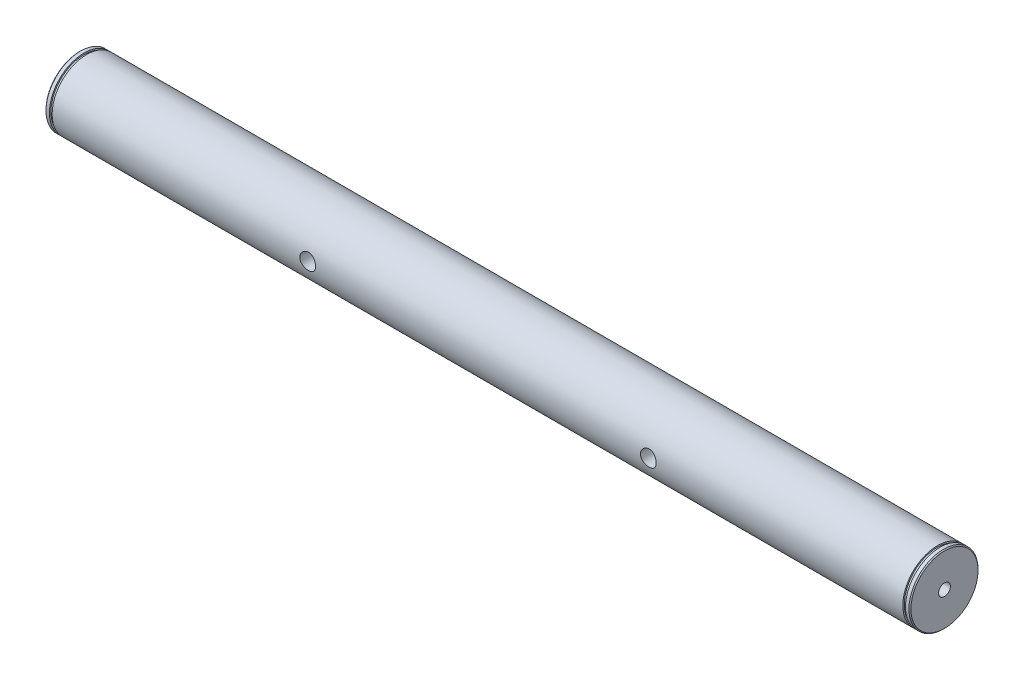
SolidWorks part; units mm, degrees
material "45"
ref_plane "前视基准面" through (0, 0, 0) normal (0, 0, 1) x (1, 0, 0)
ref_plane "上视基准面" through (0, 0, 0) normal (0, 1, 0) x (1, 0, 0)
ref_plane "右视基准面" through (0, 0, 0) normal (1, 0, 0) x (0, 0, -1)
sketch "草图1" plane through (0, 0, 0) normal (0, 0, 1) x (1, 0, 0)
  line L0 (0, 0) -> (919.604, 0) construction
  line L1 (0, 0) -> (0, 35)
  line L2 (0, 35) -> (4.5, 35)
  line L3 (876, 35) -> (876, 0)
  line L5 (4.5, 35) -> (4.5, 33.5)
  line L6 (4.5, 33.5) -> (7.2, 33.5)
  line L7 (7.2, 33.5) -> (7.2, 35)
  line L8 (7.2, 35) -> (868.8, 35)
  line L10 (871.5, 35) -> (871.5, 33.5)
  line L11 (871.5, 33.5) -> (868.8, 33.5)
  line L12 (868.8, 33.5) -> (868.8, 35)
  line L13 (871.5, 35) -> (876, 35)
  line L14 (0, 0) -> (876, 0)
  dimension "D1" = 876
  dimension "D2" = 70
  dimension "D3" = 4.5
  dimension "D4" = 4.5
  dimension "D6" = 67
  dimension "D7" = 2.7
  dimension "D11" = 2.7
  dimension "D12" = 67
revolve "旋转1" add sketch "草图1" angle 360 about L14
ref_plane "基准面1" through (0, 0, 35) normal (0, 0, 1) x (1, 0, 0)
sketch "草图2" plane through (0, 0, 35) normal (0, 0, 1) x (1, 0, 0)
  line L0 (0, 0) -> (876, 0) construction
  line L1 (0, 35) -> (0, -35) construction
  line L4 (876, -35) -> (876, 35) construction
  point P5 (266, 0)
  point P6 (611, 0)
  dimension "D1" = 266
  dimension "D2" = 345
hole_wizard "Ø16.0 (16) 直径孔2" positions "草图4" profile "草图3" hole size "Ø16.0" standard "GB"
sketch "草图4" plane through (0, 0, 35) normal (0, 0, 1) x (1, 0, 0)
  point P0 (266, 0)
  point P2 (611, 0)
sketch "草图3" plane through (266, 0, 35) normal (1, 0, 0) x (0, -1, 0)
  line L0 (0, 0) -> (0, 19.8069)
  line L1 (0, 19.8069) -> (8, 15)
  line L2 (8, 15) -> (8, 0)
  line L5 (8, 0) -> (0, 0)
  line L10 (0, 19.8069) -> (-8, 15) construction
  line L11 (0, -6.35) -> (0, 107.95) construction
  dimension "孔直径" = 16
  dimension "孔深度" = 15
  dimension "导头角度" = 118
hole_wizard "M14 螺纹孔1" positions "3D草图2" profile "草图5" tap size "M14" standard "GB"
sketch3d "3D草图2"
  circle A1 centre (876, 0, 0) radius 35 construction
  point P0 (876, 0, 0)
  point P12 (841, 0, 0)
sketch "草图5" plane through (876, 0, 0) normal (0, 1, 0) x (0, 0, -1)
  line L0 (0, 0) -> (0, 33.6052)
  line L1 (0, 33.6052) -> (6, 30)
  line L2 (6, 30) -> (6, 0)
  line L5 (6, 0) -> (0, 0)
  line L10 (0, 33.6052) -> (-6, 30) construction
  line L11 (0, -6.35) -> (0, 107.95) construction
  dimension "螺纹孔钻头直径" = 12
  dimension "螺纹孔钻头深度" = 30
  dimension "导头角度" = 118
cosmetic thread "孔螺蚊线1" parameters "D1"=20, "D2"=14
chamfer "倒角1" distance 1 angle 45 2 edges at (876, 0, 35) (0, 0, 35)
